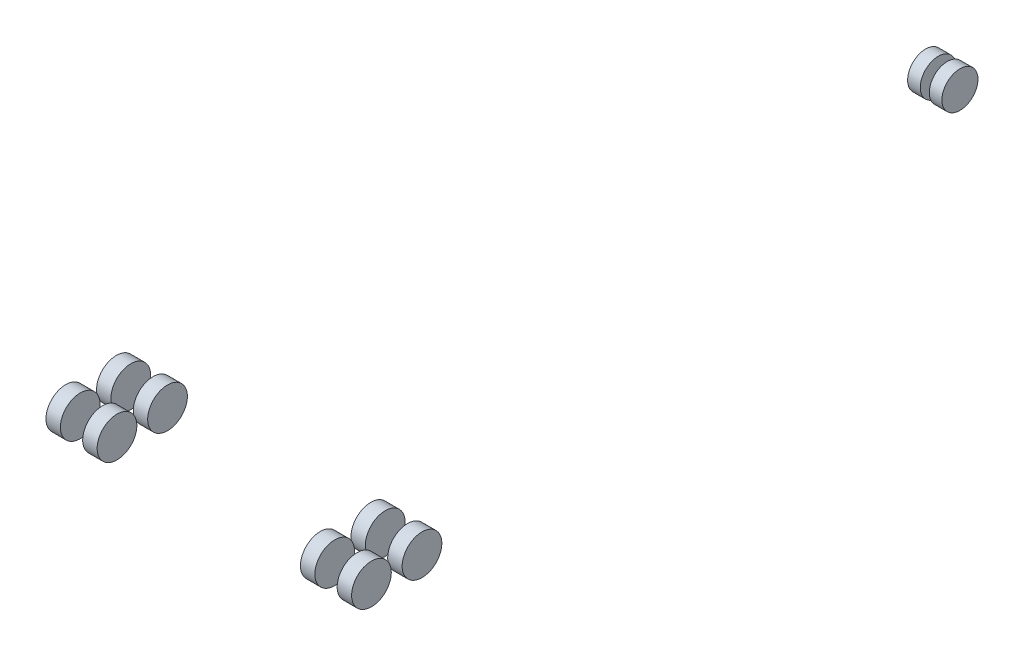
SolidWorks part; units mm, degrees
ref_plane "Front Plane" through (0, 0, 0) normal (0, 0, 1) x (1, 0, 0)
ref_plane "Top Plane" through (0, 0, 0) normal (0, 1, 0) x (1, 0, 0)
ref_plane "Right Plane" through (0, 0, 0) normal (1, 0, 0) x (0, 0, -1)
sketch "Height to CG" plane through (0, 0, 0) normal (0, 0, 1) x (1, 0, 0)
  line L0 (0, 0) -> (0, 4267.2)
  line L1 (0, 0) -> (3580.6059, 0)
  line L2 (3580.6059, 0) -> (0, 4267.2)
  dimension "D1" = 4267.2
  dimension "D2" = 50
sketch "Max bottom" plane through (0, 0, 0) normal (0, 1, 0) x (1, 0, 0)
  line L0 (0, 17678.4) -> (3580.6059, -1989.828)
  line L1 (3580.6059, -1989.828) -> (-3580.6059, -1989.828)
  line L2 (-3580.6059, -1989.828) -> (0, 17678.4)
  line L3 (0, 17678.4) -> (0, -1989.828)
  line L4 (-3063.8889, -1989.828) -> (-3063.8889, 848.4929)
  line L5 (-3580.6059, -1989.828) -> (-4097.323, -1989.828)
  line L6 (3580.6059, -1989.828) -> (4097.323, -1989.828)
  line L7 (-304.8, -1989.828) -> (-304.8, 17678.4)
  line L8 (304.8, -1989.828) -> (304.8, 17678.4)
  line L9 (-3580.6059, -1989.828) -> (2017.9975, -3009.0552)
  point P4 (0, -1989.828)
  point P8 (3063.8889, -1989.828)
  dimension "D1" = 7161.2119
  dimension "D2" = 1989.828
  dimension "D3" = 17678.4
  dimension "D4" = 516.717
  dimension "D5" = 516.717
  dimension "D6" = 516.717
  dimension "D7" = 516.717
  dimension "D8" = 304.8
  dimension "D9" = 304.8
ref_plane "Plane1" through (-3580.6059, 0, 0) normal (1, 0, 0) x (0, 0, -1)
ref_plane "Plane2" through (3580.6059, 0, 0) normal (1, 0, 0) x (0, 0, -1)
ref_plane "Plane3" through (-3063.8889, 0, 0) normal (1, 0, 0) x (0, 0, -1)
sketch "Sketch9" plane through (-3063.8889, 0, 0) normal (1, 0, 0) x (0, 0, -1)
  line L0 (-2701.028, 558.8) -> (-1278.628, 558.8) construction
  line L1 (-1989.828, 0) -> (-1989.828, 558.8) construction
  line L2 (-1989.828, 0) -> (848.4929, 0) construction
  circle A0 centre (-2701.028, 558.8) radius 558.8
  circle A1 centre (-1278.628, 558.8) radius 558.8
  point P9 (-1989.828, 558.8)
  dimension "D2" = 1117.6
  dimension "D3" = 1117.6
  dimension "D1" = 1422.4
extrude "Main tire 1" add sketch "Sketch9" along normal blind 203.2 and the other way blind 203.2
ref_plane "Plane4" through (-4097.323, 0, 0) normal (1, 0, 0) x (0, 0, -1)
sketch "Sketch10" plane through (-4097.323, 0, 0) normal (1, 0, 0) x (0, 0, -1)
  circle A0 centre (-2701.028, 558.8) radius 558.8
  circle A1 centre (-1278.628, 558.8) radius 558.8
  dimension "D2" = 1117.6
  dimension "D1" = 1117.6
extrude "Main tire 2" add sketch "Sketch10" along normal blind 203.2 and the other way blind 203.2 separate body
ref_plane "Plane5" through (3063.8889, 0, 0) normal (1, 0, 0) x (0, 0, -1)
ref_plane "Plane6" through (4097.323, 0, 0) normal (1, 0, 0) x (0, 0, -1)
sketch "Sketch12" plane through (3063.8889, 0, 0) normal (1, 0, 0) x (0, 0, -1)
  circle A0 centre (-1278.628, 558.8) radius 558.8
  circle A1 centre (-2701.028, 558.8) radius 558.8
  dimension "D2" = 1117.6
  dimension "D1" = 1117.6
extrude "Main tire 3" add sketch "Sketch12" along normal blind 203.2 and the other way blind 203.2 separate body
sketch "Sketch13" plane through (4097.323, 0, 0) normal (1, 0, 0) x (0, 0, -1)
  circle A0 centre (-2701.028, 558.8) radius 558.8
  circle A1 centre (-1278.628, 558.8) radius 558.8
  dimension "D2" = 1117.6
  dimension "D1" = 1117.6
extrude "Main tire 4" add sketch "Sketch13" along normal blind 203.2 and the other way blind 203.2 separate body
ref_plane "Plane7" through (-304.8, 0, 0) normal (1, 0, 0) x (0, 0, -1)
ref_plane "Plane8" through (304.8, 0, 0) normal (1, 0, 0) x (0, 0, -1)
sketch "Sketch14" plane through (-304.8, 0, 0) normal (1, 0, 0) x (0, 0, -1)
  line L0 (17678.4, 0) -> (17678.4, 508) construction
  line L1 (-1989.828, 0) -> (17678.4, 0) construction
  circle A0 centre (17678.4, 508) radius 508
  dimension "D1" = 1016
extrude "Nose tire 1" add sketch "Sketch14" along normal blind 177.8 and the other way blind 177.8 separate body
sketch "Sketch15" plane through (304.8, 0, 0) normal (1, 0, 0) x (0, 0, -1)
  circle A0 centre (17678.4, 508) radius 508
  dimension "D1" = 1016
extrude "Nose tire 2" add sketch "Sketch15" along normal blind 177.8 and the other way blind 177.8 separate body
ref_plane "Plane9" through (-465.4908, 0, 2556.9356) normal (0.1791, 0, -0.9838) x (0.9838, 0, 0.1791)
sketch "Check this is less than 63" plane through (-465.4908, 0, 2556.9356) normal (0.1791, 0, -0.9838) x (0.9838, 0, 0.1791)
  line L0 (-3166.3154, 0) -> (0, -4267.2)
  line L1 (-3166.3154, 0) -> (0, 0)
  dimension "D1" = 53.424
equation "\"D1@Height to CG\" = \"z\""
equation "\"z\"= 14'input from front view aircraft, 5 degree clearance"
equation "\"angle\"= 50'maximum 63 degree"
equation "\"D2@Height to CG\" = \"angle\""
equation "\"D1@Max bottom\" = \"z\" / tan ( \"angle\" )  * 2"
equation "\"Main tire diameter\"= 44 / 12"
equation "\"Main tire length\"= 16 / 12"
equation "\"D4@Max bottom\"=(tan( 36) * (\"Main tire diameter\"+1) ) * 0.5"
equation "\"D1@Sketch9\"=\"Main tire diameter\"+1"
equation "\"D2@Sketch9\"=\"Main tire diameter\""
equation "\"D3@Sketch9\"=\"Main tire diameter\""
equation "\"D1@Main tire 1\" = \"Main tire length\" * 0.5"
equation "\"D2@Main tire 1\" = \"Main tire length\" * 0.5"
equation "\"D5@Max bottom\"=\"D4@Max bottom\""
equation "\"D1@Main tire 2\" = \"Main tire length\" * 0.5"
equation "\"D2@Main tire 2\" = \"Main tire length\" * 0.5"
equation "\"D6@Max bottom\"=\"D4@Max bottom\""
equation "\"D7@Max bottom\"=\"D4@Max bottom\""
equation "\"D1@Sketch10\"=\"Main tire diameter\""
equation "\"D2@Sketch10\"=\"Main tire diameter\""
equation "\"D1@Sketch12\"=\"Main tire diameter\""
equation "\"D2@Sketch12\"=\"Main tire diameter\""
equation "\"D1@Main tire 3\" = \"Main tire length\" * 0.5"
equation "\"D2@Main tire 3\" = \"Main tire length\" * 0.5"
equation "\"D1@Sketch13\"=\"Main tire diameter\""
equation "\"D2@Sketch13\"=\"Main tire diameter\""
equation "\"D1@Main tire 4\" = \"Main tire length\" * 0.5"
equation "\"D2@Main tire 4\" = \"Main tire length\" * 0.5"
equation "\"Nose tire diameter\"= 40 / 12"
equation "\"Nose tire length\"= 14 / 12"
equation "\"D1@Sketch14\"=\"Nose tire diameter\""
equation "\"D1@Nose tire 1\" = \"Nose tire length\" * 0.5"
equation "\"D2@Nose tire 1\"=\"Nose tire length\"*0.5"
equation "\"D9@Max bottom\"=(10/12+\"Nose tire length\")*0.5"
equation "\"D8@Max bottom\"=(10/12+\"Nose tire length\")*0.5"
equation "\"D1@Sketch15\"=\"Nose tire diameter\""
equation "\"D1@Nose tire 2\" = \"Nose tire length\" * 0.5"
equation "\"D2@Nose tire 2\"=\"Nose tire length\"*0.5"
equation "\"D2@Max bottom\"=\"z\"*tan(25 )"
